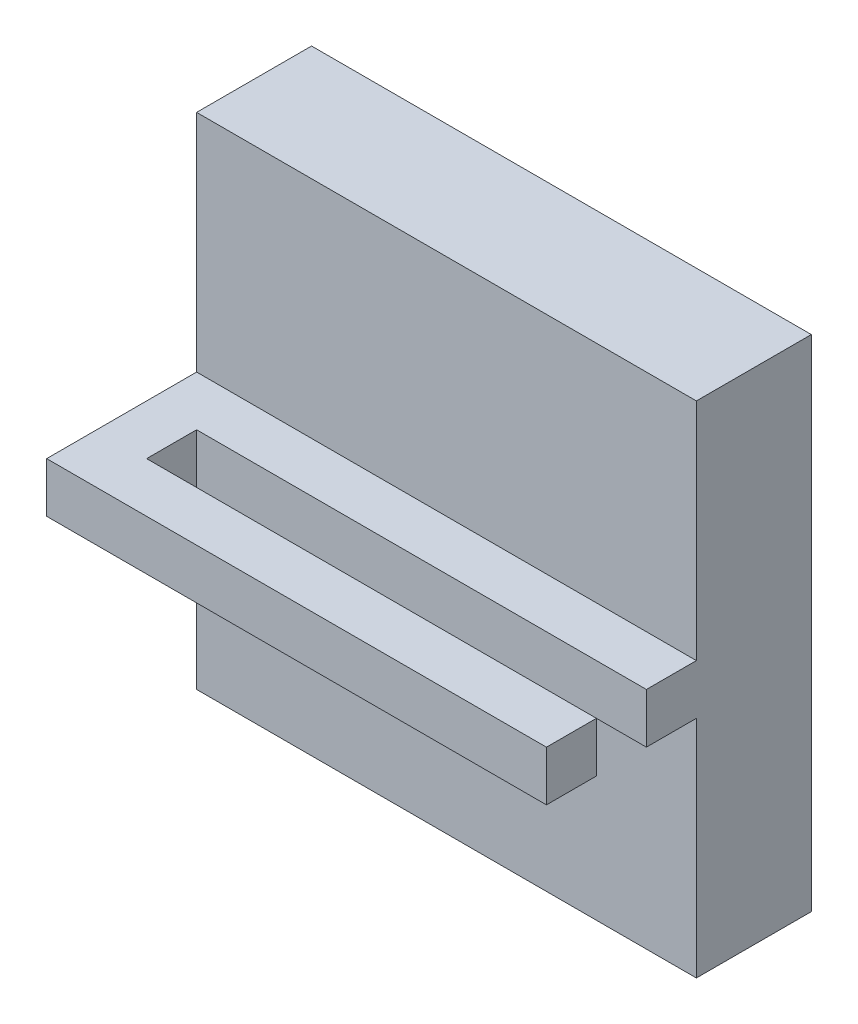
SolidWorks part; units mm, degrees
ref_plane "Front Plane" through (0, 0, 0) normal (0, 0, 1) x (1, 0, 0)
ref_plane "Top Plane" through (0, 0, 0) normal (0, 1, 0) x (1, 0, 0)
ref_plane "Right Plane" through (0, 0, 0) normal (1, 0, 0) x (0, 0, -1)
sketch "Sketch1" plane through (0, 0, 0) normal (0, 0, 1) x (1, 0, 0)
  line L0 (0, 0) -> (189.1188, 0) construction
  line L2 (0, 0) -> (100, 0)
  line L3 (0, 0) -> (0, 100)
  line L4 (0, 100) -> (100, 100)
  line L5 (100, 0) -> (100, 100)
  line L6 (0, 0) -> (100, 100) construction
  line L7 (0, 100) -> (100, 0) construction
  point P6 (50, 50)
  dimension "D1" = 100
  dimension "D2" = 100
extrude "Boss-Extrude1" add sketch "Sketch1" along normal blind 23
sketch "Sketch17" plane through (0, 0, 0) normal (1, 0, 0) x (0, 0, -1)
  line L0 (-23, 55) -> (-53, 55)
  line L1 (-23, 0) -> (-23, 100) construction
  line L2 (-53, 55) -> (-53, 45)
  line L3 (-53, 45) -> (-23, 45)
  line L4 (-23, 45) -> (-23, 55)
  line L5 (-23, 0) -> (0, 0) construction
  dimension "D1" = 30
  dimension "D2" = 10
  dimension "D3" = 55
extrude "Boss-Extrude2" add sketch "Sketch17" along normal through all
sketch "Sketch18" plane through (0, 55, 0) normal (0, 1, 0) x (1, 0, 0)
  line L0 (100, -33) -> (10, -33)
  line L1 (100, -23) -> (100, -53) construction
  line L2 (10, -33) -> (10, -43)
  line L3 (10, -43) -> (100, -43)
  line L4 (100, -43) -> (100, -33)
  line L5 (100, -23) -> (0, -23) construction
  line L6 (100, -53) -> (0, -53) construction
  line L7 (0, -23) -> (0, -53) construction
  dimension "D1" = 10
  dimension "D2" = 10
  dimension "D3" = 10
extrude "Cut-Extrude1" cut sketch "Sketch18" against normal through all
